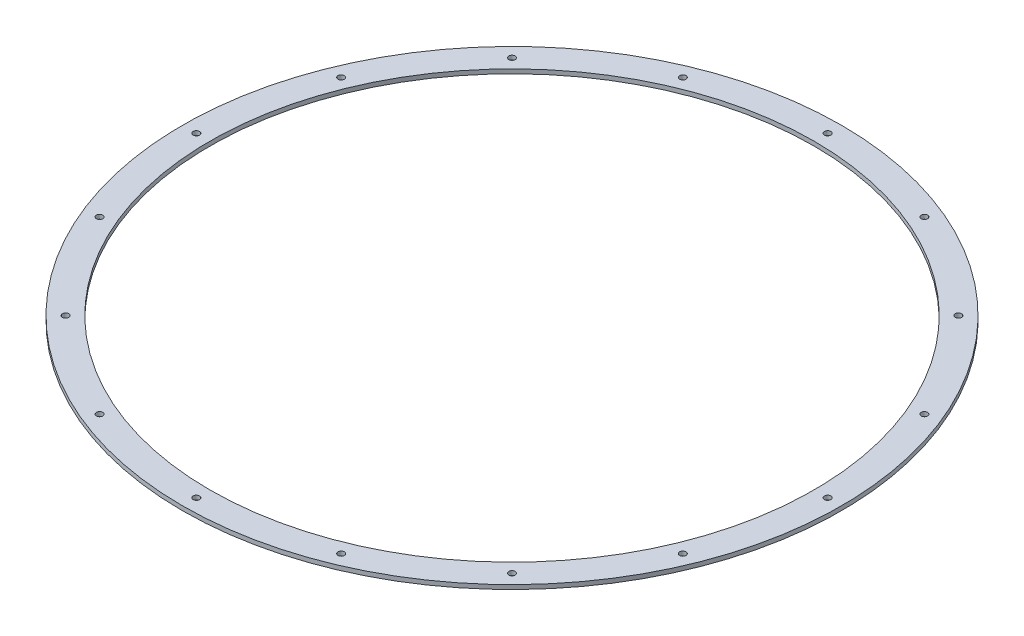
SolidWorks part; units mm, degrees
material "ASTM A36 Steel"
ref_plane "Front Plane" through (0, 0, 0) normal (0, 0, 1) x (1, 0, 0)
ref_plane "Top Plane" through (0, 0, 0) normal (0, 1, 0) x (1, 0, 0)
ref_plane "Right Plane" through (0, 0, 0) normal (1, 0, 0) x (0, 0, -1)
sketch "Sketch2" plane through (0, 0, 0) normal (0, 1, 0) x (1, 0, 0)
  circle A0 centre (0, 0) radius 462
  circle A1 centre (0, 0) radius 423.5
  dimension "D1" = 38.5
  dimension "D2" = 924
extrude "Boss-Extrude1" add sketch "Sketch2" along normal blind 6
sketch "Sketch3" plane through (0, 6, 0) normal (0, 1, 0) x (1, 0, 0)
  circle A0 centre (0, 442.5) radius 4.5
  circle A1 centre (0, 0) radius 442.5 construction
  dimension "D1" = 885
  dimension "D2" = 9
  dimension "D3" = 0
extrude "Cut-Extrude1" cut sketch "Sketch3" against normal blind 46
pattern_circular "CirPattern1" count 16 every 22.5 about axis through (0, 0, 0) along (0, 1, 0) of "Cut-Extrude1"
